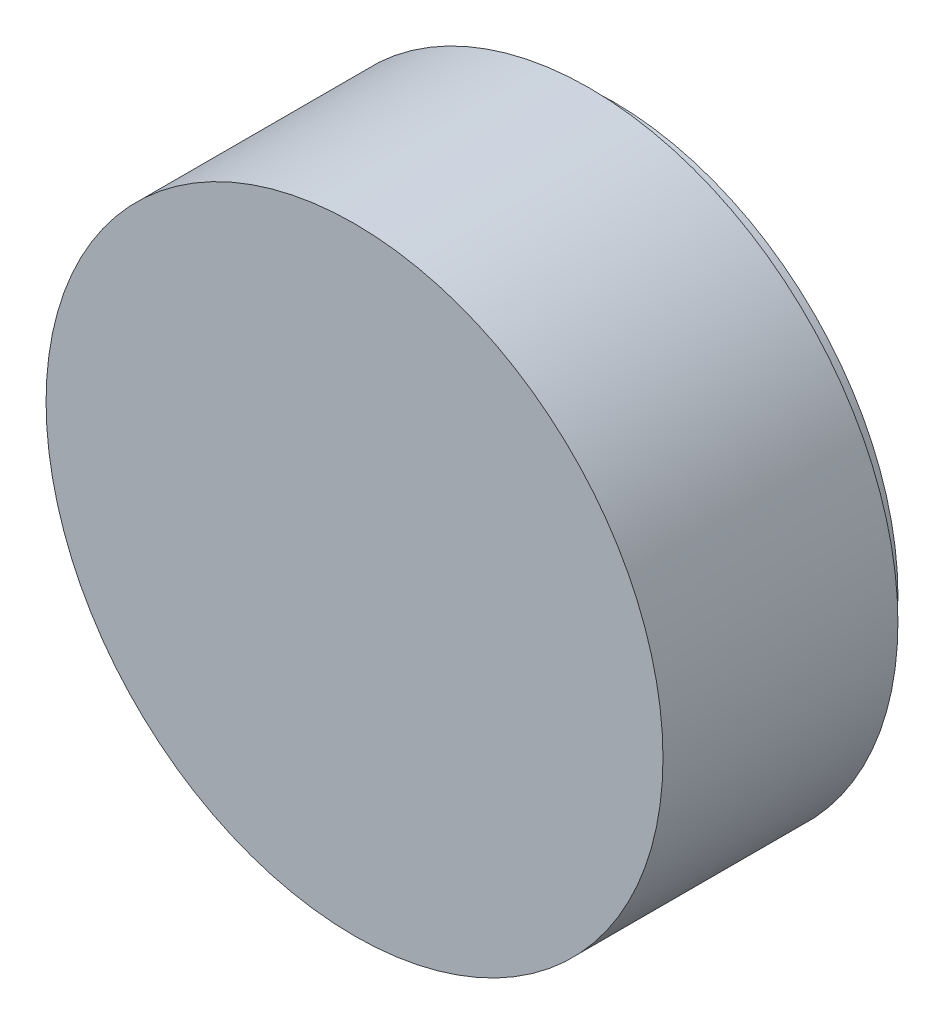
SolidWorks part; units mm, degrees
ref_plane "Front Plane" through (0, 0, 0) normal (0, 0, 1) x (1, 0, 0)
ref_plane "Top Plane" through (0, 0, 0) normal (0, 1, 0) x (1, 0, 0)
ref_plane "Right Plane" through (0, 0, 0) normal (1, 0, 0) x (0, 0, -1)
sketch "Sketch1" plane through (0, 0, 0) normal (0, 0, 1) x (1, 0, 0)
  circle A0 centre (0, 0) radius 24.257
  dimension "D1" = 48.514
extrude "Boss-Extrude1" add sketch "Sketch1" along normal blind 2
sketch "Sketch2" plane through (0, 0, 2) normal (0, 0, 1) x (1, 0, 0)
  circle A3 centre (0, 0) radius 26.257
  circle A4 centre (0, 0) radius 26.257
  dimension "D1" = 2
extrude "Boss-Extrude2" add sketch "Sketch2" along normal blind 20
